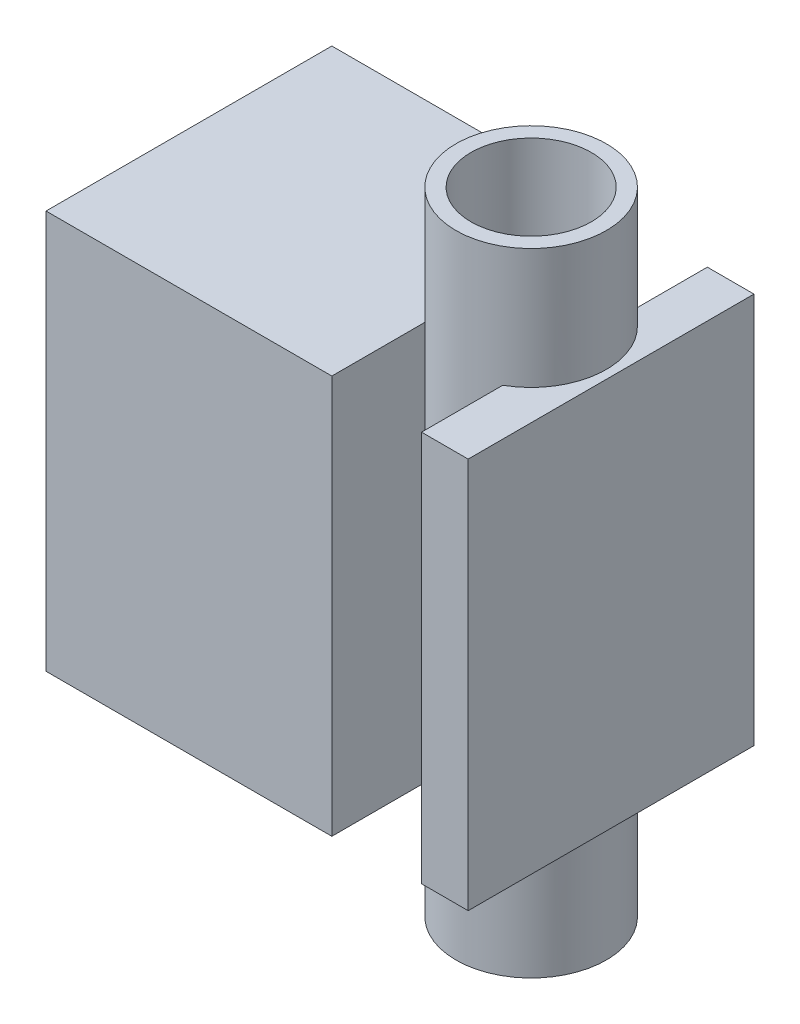
SolidWorks part; units mm, degrees
ref_plane "Front Plane" through (0, 0, 0) normal (0, 0, 1) x (1, 0, 0)
ref_plane "Top Plane" through (0, 0, 0) normal (0, 1, 0) x (1, 0, 0)
ref_plane "Right Plane" through (0, 0, 0) normal (1, 0, 0) x (0, 0, -1)
sketch "Sketch2" plane through (0, 0, 0) normal (0, 0, 1) x (1, 0, 0)
  line L1 (-107.7769, 29.5661) -> (-69.7769, 29.5661)
  line L2 (-107.7769, 29.5661) -> (-107.7769, -23.4339)
  line L3 (-107.7769, -23.4339) -> (-69.7769, -23.4339)
  line L5 (-49.7769, 45.0661) -> (-69.7769, 45.0661)
  line L6 (-69.7769, 45.0661) -> (-69.7769, 29.5661)
  line L8 (-49.7769, -38.9339) -> (-69.7769, -38.9339)
  line L9 (-69.7769, -38.9339) -> (-69.7769, -23.4339)
  line L10 (-49.7769, 45.0661) -> (-49.7769, -38.9339)
  dimension "D1" = 53
  dimension "D2" = 84
  dimension "D4" = 20
extrude "Boss-Extrude1" add sketch "Sketch2" along normal blind 38
sketch "Sketch3" plane through (0, 45.0661, 0) normal (0, 1, 0) x (1, 0, 0)
  line L0 (-49.7769, -38) -> (-49.7769, 0) construction
  line L1 (-49.7769, -38) -> (-69.7769, -38) construction
  circle A0 centre (-62.7769, -18.5) radius 10
  point P6 (-62.7769, -18.5)
  dimension "D1" = 13
  dimension "D2" = 19.5
extrude "Boss-Extrude4" add sketch "Sketch3" against normal up to vertex (84 mm away) contours A0
sketch "Sketch4" plane through (0, 45.0661, 0) normal (0, 1, 0) x (1, 0, 0)
  circle A0 centre (-62.7769, -18.5) radius 8
extrude "Cut-Extrude1" cut sketch "Sketch4" against normal through all both and the other way through all
sketch "Sketch5" plane through (0, 45.0661, 0) normal (0, 1, 0) x (1, 0, 0)
  line L2 (-49.7769, 0) -> (-69.7769, 0) construction
  line L6 (-49.7769, -38) -> (-69.7769, -38) construction
  line L9 (-56.4437, 0) -> (-69.7769, 0)
  line L10 (-69.7769, 0) -> (-69.7769, -11.3586)
  line L11 (-69.7769, -25.6414) -> (-69.7769, -38)
  line L12 (-69.7769, -38) -> (-56.4437, -38)
  line L13 (-56.4437, 0) -> (-49.7769, 0)
  line L14 (-49.7769, 0) -> (-49.7769, -38)
  line L15 (-49.7769, -38) -> (-56.4437, -38)
  arc A2 (-69.7769, -25.6414) -> (-69.7769, -11.3586) centre (-62.7769, -18.5) ccw
extrude "Cut-Extrude2" cut sketch "Sketch5" against normal through all both and the other way through all
sketch "Sketch6" plane through (0, 45.0661, 0) normal (0, 1, 0) x (1, 0, 0)
  line L0 (-57.85, 0) -> (-52.7857, 0)
  line L3 (-52.7857, -38) -> (-57.85, -38)
  line L4 (-57.85, 0) -> (-57.85, -12.1971)
  line L5 (-57.85, -24.8029) -> (-57.85, -38)
  line L6 (-52.7857, 0) -> (-51.651, 0)
  line L7 (-51.651, 0) -> (-51.651, -38)
  line L8 (-51.651, -38) -> (-52.7857, -38)
  arc A0 (-57.85, -24.8029) -> (-57.85, -12.1971) centre (-62.7769, -18.5) ccw
extrude "Boss-Extrude5" add sketch "Sketch6" against normal blind 52 from offset 16
